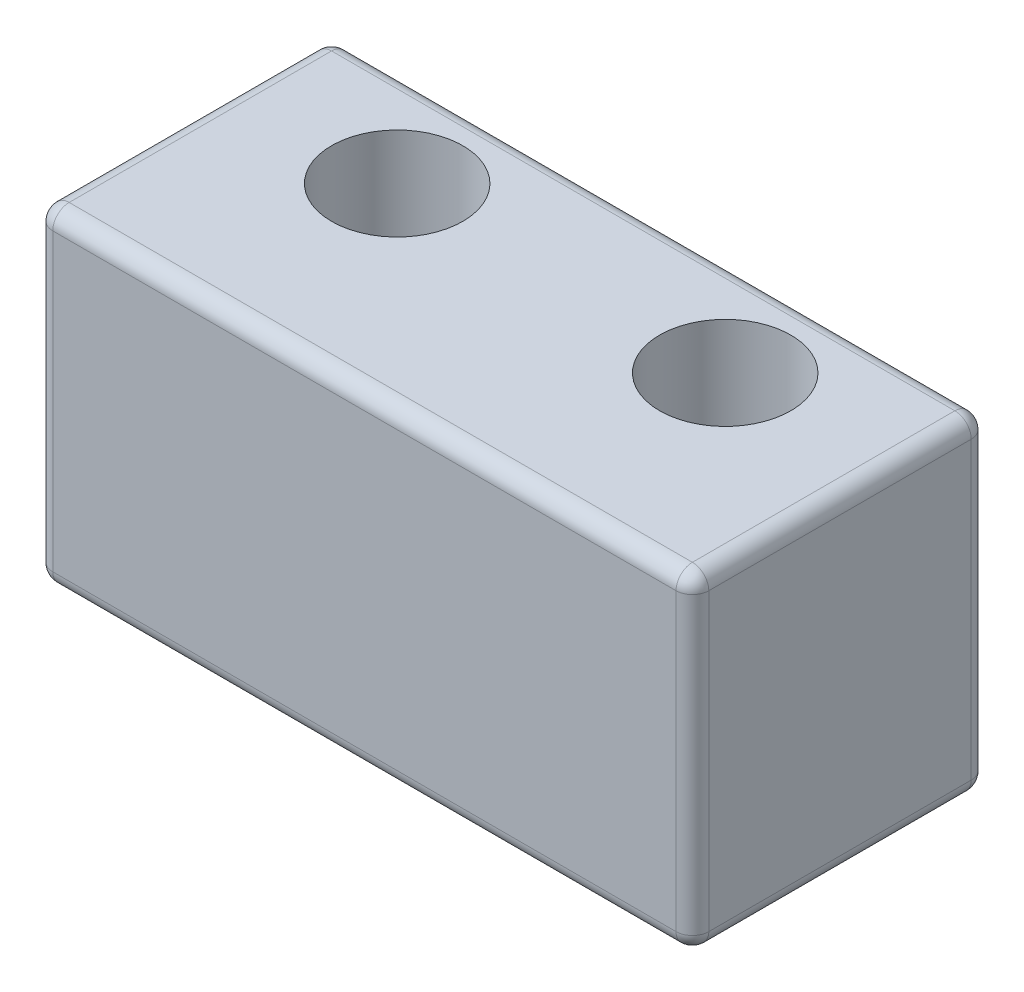
SolidWorks part; units mm, degrees
ref_plane "Front Plane" through (0, 0, 0) normal (0, 0, 1) x (1, 0, 0)
ref_plane "Top Plane" through (0, 0, 0) normal (0, 1, 0) x (1, 0, 0)
ref_plane "Right Plane" through (0, 0, 0) normal (1, 0, 0) x (0, 0, -1)
sketch "Sketch1" plane through (0, 0, 0) normal (0, 1, 0) x (1, 0, 0)
  line L1 (-9.1379, 3.1466) -> (10.8621, 3.1466)
  line L2 (-9.1379, 3.1466) -> (-9.1379, -1.8534)
  line L4 (10.8621, 3.1466) -> (10.8621, -1.8534)
  line L6 (-9.1379, -1.8534) -> (-9.1379, -5.8534)
  line L7 (-9.1379, -5.8534) -> (10.8621, -5.8534)
  line L8 (10.8621, -1.8534) -> (10.8621, -5.8534)
  dimension "D1" = 5
  dimension "D2" = 20
  dimension "D3" = 4
extrude "Boss-Extrude1" add sketch "Sketch1" along normal blind 10
sketch "Sketch2" plane through (0, 10, 0) normal (0, 1, 0) x (1, 0, 0)
  line L0 (-9.1379, 3.1466) -> (-9.1379, 0.1466) construction
  line L1 (-9.1379, 3.1466) -> (-9.1379, -5.8534) construction
  line L2 (-9.1379, 0.1466) -> (-6.1379, 0.1466) construction
  line L3 (10.8621, -5.8534) -> (10.8621, 3.1466) construction
  line L4 (10.8621, 3.1466) -> (10.8621, 0.1466) construction
  line L5 (-2.1379, 0.1466) -> (3.8621, 0.1466)
  line L6 (-2.1379, 0.1466) -> (3.8621, 0.1466) construction
  line L7 (7.8621, 0.1466) -> (10.8621, 0.1466) construction
  circle A2 centre (-4.1379, 0.1466) radius 2
  circle A3 centre (5.8621, 0.1466) radius 2
  point P13 (0.8621, 0.1466)
extrude "Cut-Extrude1" cut sketch "Sketch2" against normal blind 5
fillet "Fillet2" radius 0.5 12 edges at (10.8621, 0, 1.3534) (0.8621, 0, 5.8534) (0.8621, 0, -3.1466) (-9.1379, 0, 1.3534) (-9.1379, 5, -3.1466) (10.8621, 10, 1.3534) (10.8621, 5, -3.1466) (10.8621, 5, 5.8534) (-9.1379, 5, 5.8534) (-9.1379, 10, 1.3534) (0.8621, 10, 5.8534) (0.8621, 10, -3.1466)
